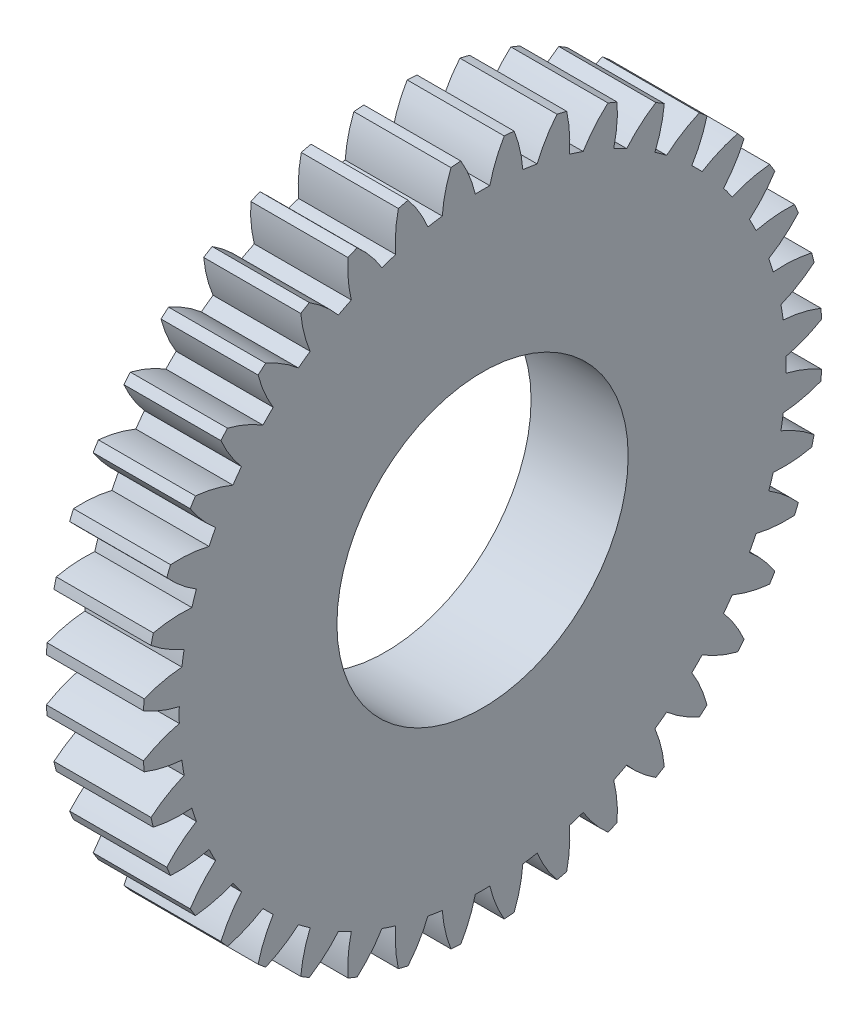
SolidWorks part; units mm, degrees
ref_plane "Plane1" through (0, 0, 0) normal (0, 0, 1) x (1, 0, 0)
ref_plane "Plane2" through (0, 0, 0) normal (0, 1, 0) x (1, 0, 0)
ref_plane "Plane3" through (0, 0, 0) normal (1, 0, 0) x (0, 0, -1)
sketch "HoldingSke" plane through (0, 0, 0) normal (0, 1, 0) x (1, 0, 0)
  line L0 (0, 0) -> (1.5321, -1.2856)
  line L1 (-15, 0) -> (100, 0) construction
  line L2 (0, 0) -> (-2.1039, 2.3779)
  line L3 (0, 0) -> (-11.863, 4.5341)
  line L4 (0, 0) -> (6.6156, 5.5511)
  line L5 (0, 0) -> (-46.8476, -17.4728)
  line L6 (0, 0) -> (-2.4869, -1.6779)
  line L7 (-2.1039, 2.3779) -> (8.6586, 51.2059)
  line L8 (-76.2, 54.61) -> (-74.8, 54.61)
  line L9 (-71.009, 38.7566) -> (-53.1078, 45.2721)
  line L10 (-76.2, 71.12) -> (104.1128, 71.12)
  line L11 (0, 0) -> (-3, 0)
  line L12 (-76.2, 101.6) -> (-76.181, 101.6)
  line L13 (24.9733, 27.94) -> (52.9518, 28.4284)
  line L14 (24.9733, 27.94) -> (24.9743, 27.94)
  line L15 (24.9733, 27.94) -> (100.4006, 29.5858)
  line L16 (-63.627, -0.5) -> (-12.827, -0.5)
  circle A0 centre (0, 0) radius 4.5
  circle A1 centre (0, 0) radius 9.374
  circle A2 centre (0, 0) radius 37.5
  circle A3 centre (0, 0) radius 4.5
  dimension "MHD" = 18.748
  dimension "Hub_dia" = 75
  dimension "Bore" = 9
  dimension "MBD" = 9
  dimension "Num_teeth" = 40
  dimension "Pitch" = 2
  dimension "Overall_len" = 50
  dimension "Show_teeth" = 40
  dimension "Thickness" = 3
  dimension "OAL" = 50.0001
  dimension "T_dim" = 1.4
  dimension "Ap" = 20
  dimension "H" = 19.05
  dimension "Pitch_radius" = 180.3128
  dimension "Width" = 3
  dimension "Backlash" = 0.019
  dimension "Addendum_fac" = 1
  dimension "Dedendum_fac" = 1.25
  dimension "Clearance_fac" = 0.25
  dimension "Dedendum_add" = 0.001
  dimension "Module" = 0.5
sketch "BasProSke" plane through (0, 0, 0) normal (0, 1, 0) x (1, 0, 0)
  line L0 (-10, 0) -> (60, 0) construction
  line L1 (0, 0) -> (0, 10.5)
  line L2 (0, 0) -> (3, 0)
  line L3 (3, 0) -> (3, 10.5)
  line L4 (3, 10.5) -> (0, 10.5)
  dimension "Thickness" = 3
  dimension "Diameter" = 21
revolve "Base-Revolve" add sketch "BasProSke" angle 360 about L0
sketch "TooCutSke" plane through (0, 0, 0) normal (1, 0, 0) x (0, 0, -1)
  line L1 (0, 0) -> (0, 107) construction
  line L2 (0, 0) -> (-0.4258, 9.9909) construction
  line L3 (0, 0) -> (-1.5682, 19.9255) construction
  line L4 (-0.4258, 9.9909) -> (-0.7841, 9.9627) construction
  arc A0 (0.2242, 9.3713) -> (-0.2242, 9.3713) centre (0, 0) ccw
  arc A1 (0.6847, 10.5031) -> (-0.6847, 10.5031) centre (0, 0) ccw
  circle A2 centre (0, 0) radius 10 construction
  circle A3 centre (0, 0) radius 9.3969 construction
  arc A4 (-0.2242, 9.3713) -> (-0.6847, 10.5031) centre (-4.1161, 8.4475) ccw
  arc A5 (0.6847, 10.5031) -> (0.2242, 9.3713) centre (4.1161, 8.4475) ccw
  dimension "Root_dia" = 18.748
  dimension "Overcut_dia" = 21.0508
  dimension "Pitch_dia" = 20
  dimension "Base_dia" = 18.7939
  dimension "Flank_rad" = 4
  dimension "Half_ang" = 4.5
  dimension "Half_CT" = 0.3593
extrude "ToothCut" cut sketch "TooCutSke" along normal through all
fillet "Breaks" [suppressed] radius 0.01
fillet "RootFillets" [suppressed] radius 0.126
pattern_circular "TeethCuts" count 40 every 9 about axis through (-10, 0, 0) along (1, 0, 0) of "ToothCut", "RootFillets", "Breaks"
sketch "HubNeaOneSke" plane through (0, 0, 0) normal (-1, 0, 0) x (0, 0, 1)
  circle A0 centre (0, 0) radius 9.374
  dimension "Diameter" = 18.748
extrude "HubNearOne" [suppressed] add sketch "HubNeaOneSke" along normal blind 47.0001
sketch "HubNeaBotSke" plane through (0, 0, 0) normal (-1, 0, 0) x (0, 0, 1)
  circle A0 centre (0, 0) radius 9.374
  dimension "Diameter" = 18.748
extrude "HubNearBoth" [suppressed] add sketch "HubNeaBotSke" along normal blind 23.5
ref_plane "FarPln" through (3, 0, 0) normal (1, 0, 0) x (0, 0, -1)
sketch "HubFarSke" plane through (3, 0, 0) normal (1, 0, 0) x (0, 0, -1)
  circle A0 centre (0, 0) radius 9.374
  dimension "Diameter" = 18.748
extrude "HubFar" [suppressed] add sketch "HubFarSke" along normal blind 23.5
sketch "BorSke" plane through (0, 0, 0) normal (1, 0, 0) x (0, 0, -1)
  circle A0 centre (0, 0) radius 4.5
  dimension "Diameter" = 9
extrude "Bore" cut sketch "BorSke" along normal mid plane 100.0001
sketch "KeySke" plane through (0, 0, 0) normal (1, 0, 0) x (0, 0, -1)
  line L0 (-1.5, 0) -> (-1.5, 5.9)
  line L1 (-1.5, 5.9) -> (1.5, 5.9)
  line L2 (1.5, 5.9) -> (1.5, 0)
  line L3 (0, 0) -> (0, 34) construction
  line L4 (-1.5, 0) -> (1.5, 0)
  dimension "Width" = 3
  dimension "Offset" = 5.9
extrude "Keyway" [suppressed] cut sketch "KeySke" along normal mid plane 100.0001
pattern_circular "Keyway2" [suppressed] count 2 every 90 about axis through (-10, 0, 0) along (1, 0, 0)
equation "' \"Module@HoldingSke\" = 6.35"
equation "' \"Num_teeth@HoldingSke\" = 12"
equation "' \"Ap@HoldingSke\" =  20"
equation "' \"Ap@HoldingSke\" = 20"
equation "' \"Width@HoldingSke\" = 0.5 * 25.4"
equation "' \"Hub_dia@HoldingSke\"= 1 * 25.4"
equation "' \"Hub_dia@HoldingSke\" = 1 * 25.4"
equation "' \"Overall_len@HoldingSke\" = 1.0 * 25.4"
equation "' \"Bore@HoldingSke\" = 0.75 * 25.4"
equation "' \"T_dim@HoldingSke\" = 0.1 * 25.4"
equation "' \"Width@KeySke\" = 0.25 * 25.4"
equation "' \"Show_teeth@HoldingSke\" = 13"
equation "' \"Backlash@HoldingSke\" = 0.009 * 25.4"
equation "' \"Addendum_fac@HoldingSke\" = 1.0"
equation "' \"Dedendum_fac@HoldingSke\" = 1.25"
equation "' \"Dedendum_add@HoldingSke\" = 0.00005 * 25.4"
equation "' \"Clearance_fac@HoldingSke\" = 0.25"
equation "\"Pitch@HoldingSke\" = 1 / \"Module@HoldingSke\""
equation "\"Overcut_dia@TooCutSke\" = (\"Num_teeth@HoldingSke\" + 2 * \"Addendum_fac@HoldingSke\") / \"Pitch@HoldingSke\" + 0.002 * 25.4"
equation "\"Pitch_dia@TooCutSke\" = \"Num_teeth@HoldingSke\" / \"Pitch@HoldingSke\""
equation "\"Base_dia@TooCutSke\" = \"Num_teeth@HoldingSke\" / \"Pitch@HoldingSke\" * cos((\"Ap@HoldingSke\"  * 3.14159265 / 180))"
equation "\"Root_dia@TooCutSke\" = (\"Num_teeth@HoldingSke\" + 2) / \"Pitch@HoldingSke\" - 2 * (\"Addendum_fac@HoldingSke\" + \"Dedendum_fac@HoldingSke\") / \"Pitch@HoldingSke\" - \"Dedendum_add@HoldingSke\" * 2"
equation "\"Half_ang@TooCutSke\" = 180 / \"Num_teeth@HoldingSke\""
equation "\"Half_CT@TooCutSke\" = \"Num_teeth@HoldingSke\" / \"Pitch@HoldingSke\" * sin((3.14159265 / 2 / \"Num_teeth@HoldingSke\")) / 2 - 7 * \"Backlash@HoldingSke\" / 4"
equation "\"Flank_rad@TooCutSke\" = \"Num_teeth@HoldingSke\" / \"Pitch@HoldingSke\" / 5"
equation "\"Radius@RootFillets\" = \"Clearance_fac@HoldingSke\" / \"Pitch@HoldingSke\" + \"Dedendum_add@HoldingSke\""
equation "\"Break_rad@Breaks\" = 0.02 / \"Pitch@HoldingSke\""
equation "\"Thickness@HoldingSke\" = \"Width@HoldingSke\""
equation "\"OAL@HoldingSke\" = \"Thickness@HoldingSke\""
equation "\"MHD@HoldingSke\" = (\"Num_teeth@HoldingSke\" + 2) / \"Pitch@HoldingSke\" - 2 * (\"Addendum_fac@HoldingSke\" + \"Dedendum_fac@HoldingSke\")  / \"Pitch@HoldingSke\" - \"Dedendum_add@HoldingSke\" * 2"
equation "\"MBD@HoldingSke\" = (\"Num_teeth@HoldingSke\" + 2) / \"Pitch@HoldingSke\" - 2 * (\"Addendum_fac@HoldingSke\" + \"Dedendum_fac@HoldingSke\")  / \"Pitch@HoldingSke\" - \"Dedendum_add@HoldingSke\" * 2 - 0.002 * 25.4"
equation "\"MHD@HoldingSke\" = ((sgn( \"MHD@HoldingSke\" - \"Hub_dia@HoldingSke\" )-1)*( \"MHD@HoldingSke\" - \"Hub_dia@HoldingSke\" ))/-2+ \"Hub_dia@HoldingSke\""
equation "\"MBD@HoldingSke\" = ((sgn( \"MBD@HoldingSke\" - \"Bore@HoldingSke\" )-1)*( \"MBD@HoldingSke\" - \"Bore@HoldingSke\" ))/-2+ \"Bore@HoldingSke\""
equation "\"OAL@HoldingSke\" = ((sgn( \"OAL@HoldingSke\" - \"Overall_len@HoldingSke\" )+1)*( \"OAL@HoldingSke\" - \"Overall_len@HoldingSke\" ))/2 + \"Overall_len@HoldingSke\" + 0.000002 * 25.4"
equation "\"Num_teeth@TeethCuts\" = int( \"Show_teeth@HoldingSke\" ) + 1"
equation "\"Num_teeth@TeethCuts\" = ((sgn( \"Num_teeth@TeethCuts\" - \"Num_teeth@HoldingSke\" )-1)*( \"Num_teeth@TeethCuts\" - \"Num_teeth@HoldingSke\" ))/-2+ \"Num_teeth@HoldingSke\""
equation "\"Num_teeth@TeethCuts\" = ((sgn( \"Num_teeth@TeethCuts\" - 2.0)+1)*( \"Num_teeth@TeethCuts\" - 2.0))/2 +2.0"
equation "\"Angle@TeethCuts\" = 360.0 / \"Num_teeth@HoldingSke\""
equation "\"Diameter@BasProSke\" = (\"Num_teeth@HoldingSke\" + 2 * \"Addendum_fac@HoldingSke\") / \"Pitch@HoldingSke\""
equation "\"Thickness@BasProSke\"  = \"Thickness@HoldingSke\""
equation "' \"Fillet_rad@BasProSke\" =  \"Thickness@HoldingSke\" * 0.05"
equation "' \"Fillet_rad@BasProSke\" = \"Thickness@HoldingSke\" * 0.05"
equation "\"MHD@HoldingSke\" = ((sgn( \"MHD@HoldingSke\" - \"Root_dia@TooCutSke\" )-1)*( \"MHD@HoldingSke\" - \"Root_dia@TooCutSke\" ))/-2+ \"Root_dia@TooCutSke\""
equation "\"Diameter@HubNeaOneSke\" = \"MHD@HoldingSke\""
equation "\"Length@HubNearOne\" = \"OAL@HoldingSke\" - \"Thickness@BasProSke\""
equation "\"Diameter@HubNeaBotSke\" = \"MHD@HoldingSke\""
equation "\"Length@HubNearBoth\" = ( \"OAL@HoldingSke\" - \"Thickness@BasProSke\" ) / 2.0"
equation "\"Thickness@FarPln\" = \"Thickness@BasProSke\""
equation "\"Diameter@HubFarSke\" = \"MHD@HoldingSke\""
equation "\"Length@HubFar\" = ( \"OAL@HoldingSke\" - \"Thickness@BasProSke\" ) / 2.0"
equation "\"Diameter@BorSke\" = \"MBD@HoldingSke\""
equation "\"D1@Bore\" = \"OAL@HoldingSke\" * 2.0"
equation "\"D1@Keyway\" = \"OAL@HoldingSke\" * 2.0"
equation "\"Offset@KeySke\" = \"T_dim@HoldingSke\" + \"MBD@HoldingSke\" / 2.0"
